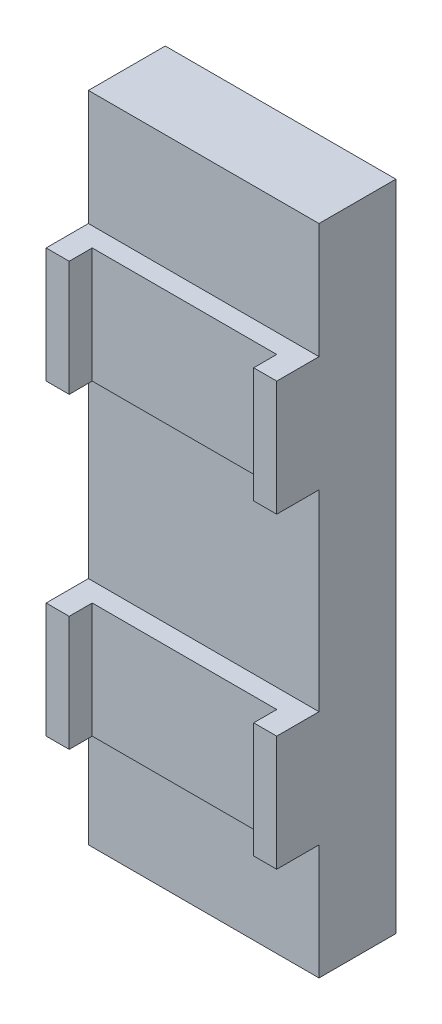
SolidWorks part; units mm, degrees
ref_plane "Front Plane" through (0, 0, 0) normal (0, 0, 1) x (1, 0, 0)
ref_plane "Top Plane" through (0, 0, 0) normal (0, 1, 0) x (1, 0, 0)
ref_plane "Right Plane" through (0, 0, 0) normal (1, 0, 0) x (0, 0, -1)
sketch "Sketch1" plane through (0, 0, 0) normal (0, 0, 1) x (1, 0, 0)
  line L1 (0, 0) -> (30, 0)
  line L2 (0, 0) -> (0, 85)
  line L3 (0, 85) -> (30, 85)
  line L4 (30, 0) -> (30, 85)
  dimension "D1" = 85
  dimension "D2" = 30
extrude "Boss-Extrude1" add sketch "Sketch1" along normal blind 10
sketch "Sketch2" plane through (0, 0, 10) normal (0, 0, 1) x (1, 0, 0)
  line L0 (0, 85) -> (0, 0) construction
  line L1 (0, 70) -> (30, 70)
  line L2 (0, 70) -> (0, 55)
  line L3 (0, 55) -> (30, 55)
  line L4 (30, 70) -> (30, 55)
  line L5 (30, 0) -> (30, 85) construction
  line L6 (0, 42.5) -> (30, 42.5) construction
  line L7 (30, 85) -> (0, 85) construction
  line L8 (30, 15) -> (30, 30)
  line L9 (0, 30) -> (30, 30)
  line L10 (0, 15) -> (0, 30)
  line L11 (0, 15) -> (30, 15)
  dimension "D1" = 15
  dimension "D2" = 15
extrude "Boss-Extrude2" add sketch "Sketch2" along normal blind 2.5
sketch "Sketch3" plane through (0, 0, 12.5) normal (0, 0, 1) x (1, 0, 0)
  line L0 (0, 55) -> (30, 55) construction
  line L1 (30, 70) -> (27, 70)
  line L2 (30, 70) -> (30, 55)
  line L3 (30, 55) -> (27, 55)
  line L4 (27, 70) -> (27, 55)
  line L5 (0, 15) -> (30, 15) construction
  line L6 (30, 30) -> (27, 30)
  line L7 (30, 30) -> (30, 15)
  line L8 (30, 15) -> (27, 15)
  line L9 (27, 30) -> (27, 15)
  line L10 (15, 70) -> (15, 15) construction
  line L11 (30, 70) -> (0, 70) construction
  line L12 (3, 30) -> (3, 15)
  line L13 (0, 15) -> (3, 15)
  line L14 (0, 30) -> (0, 15)
  line L15 (0, 30) -> (3, 30)
  line L16 (3, 70) -> (3, 55)
  line L17 (0, 55) -> (3, 55)
  line L18 (0, 70) -> (0, 55)
  line L19 (0, 70) -> (3, 70)
  dimension "D1" = 3
  dimension "D2" = 3
extrude "Boss-Extrude3" add sketch "Sketch3" along normal blind 3
